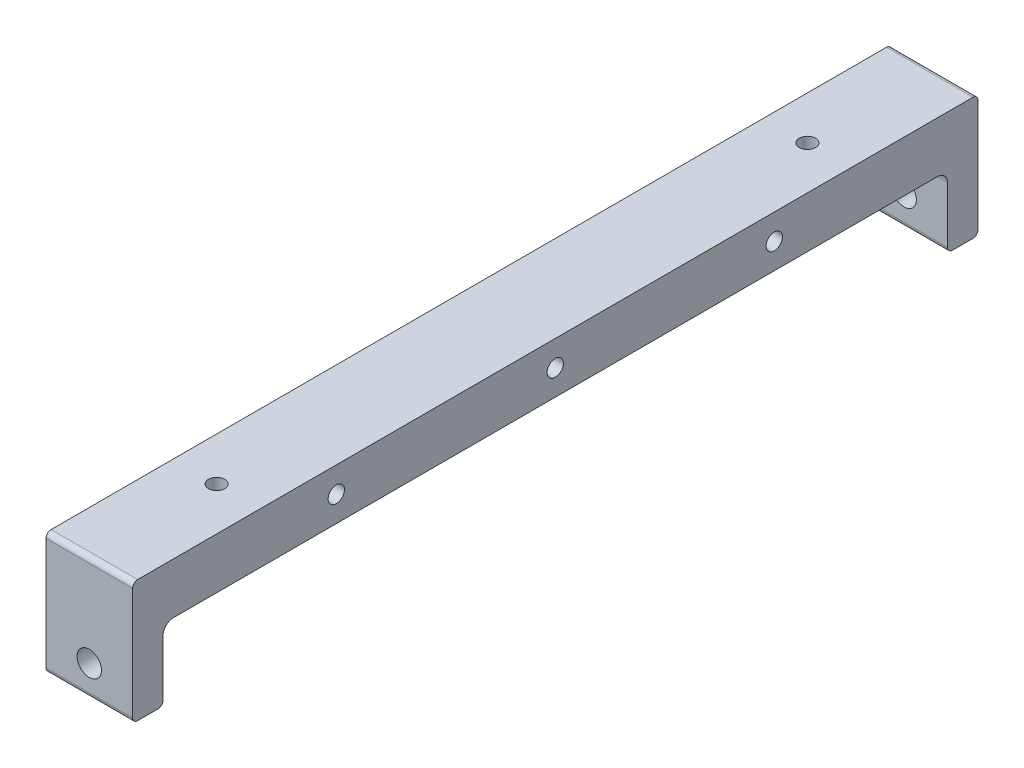
SolidWorks part; units mm, degrees
material "6061 Alloy"
ref_plane "Frontal" through (0, 0, 0) normal (0, 0, 1) x (1, 0, 0)
ref_plane "Superior" through (0, 0, 0) normal (0, 1, 0) x (1, 0, 0)
ref_plane "Direito" through (0, 0, 0) normal (1, 0, 0) x (0, 0, -1)
sketch "Sketch1" plane through (0, 0, 0) normal (0, 0, 1) x (1, 0, 0)
  line L1 (-4.25, -6) -> (4.25, -6)
  line L2 (-4.25, -6) -> (-4.25, 6)
  line L3 (-4.25, 6) -> (4.25, 6)
  line L4 (4.25, -6) -> (4.25, 6)
  line L5 (-4.25, -6) -> (4.25, 6) construction
  line L6 (-4.25, 6) -> (4.25, -6) construction
  point P0 (0, 0)
  dimension "D1" = 8.5
  dimension "D2" = 12
extrude "Boss-Extrude1" add sketch "Sketch1" along normal mid plane 83
sketch "Sketch2" plane through (4.25, 0, 0) normal (1, 0, 0) x (0, 0, -1)
  line L0 (-37.5, 1) -> (37.5, 1)
  line L1 (38.5, 0) -> (38.5, -6)
  line L2 (-41.5, -6) -> (41.5, -6) construction
  line L3 (38.5, -6) -> (-38.5, -6)
  line L4 (-38.5, -6) -> (-38.5, 0)
  line L5 (-41.5, 6) -> (41.5, 6) construction
  line L6 (-41.5, -6) -> (-41.5, 6) construction
  line L7 (41.5, -6) -> (41.5, 6) construction
  arc A0 (37.5, 1) -> (38.5, 0) centre (37.5, 0) cw
  arc A1 (-37.5, 1) -> (-38.5, 0) centre (-37.5, 0) ccw
  dimension "D4" = 1
  dimension "D5" = 1
  dimension "D1" = 5
  dimension "D2" = 3
  dimension "D3" = 3
extrude "Cut-Extrude1" cut sketch "Sketch2" against normal through all
fillet "Fillet1" radius 0.5 6 edges at (0, -6, 38.5) (0, -6, 41.5) (0, -6, -38.5) (0, -6, -41.5) (0, 6, 41.5) (0, 6, -41.5)
hole_wizard "M2 Hole1-R" positions "Sketch19" profile "Sketch18" hole size "M2" standard "DIN"
sketch "Sketch19" plane through (4.25, 0, 0) normal (1, 0, 0) x (0, 0, -1)
  line L0 (-41.5, -5.5) -> (-41.5, 5.5) construction
  line L1 (41.5, -5.5) -> (41.5, 5.5) construction
  line L2 (-41, 6) -> (41, 6) construction
  point P0 (21.5, 3.5)
  point P2 (-21.5, 3.5)
  dimension "D1" = 20
  dimension "D2" = 20
  dimension "D3" = 2.5
sketch "Sketch18" plane through (4.25, 3.5, -21.5) normal (0, 1, 0) x (0, 0, -1)
  line L0 (0, 0) -> (0, 5.4807)
  line L1 (0, 5.4807) -> (0.8, 5)
  line L2 (0.8, 5) -> (0.8, 0)
  line L5 (0.8, 0) -> (0, 0)
  line L10 (0, 5.4807) -> (-0.8, 5) construction
  line L11 (0, -6.35) -> (0, 107.95) construction
  dimension "Hole Dia." = 1.6
  dimension "Hole Depth" = 5
  dimension "Drill Angle" = 118
hole_wizard "M2 Hole2-T" positions "Sketch13" profile "Sketch12" hole size "M2" standard "DIN"
sketch "Sketch13" plane through (4.25, 0, 0) normal (1, 0, 0) x (0, 0, -1)
  line L0 (-41, 6) -> (41, 6) construction
  point P0 (0, 3.5)
  dimension "D1" = 2.5
sketch "Sketch12" plane through (4.25, 3.5, 0) normal (0, 1, 0) x (0, 0, -1)
  line L0 (0, 0) -> (0, 4.4807)
  line L1 (0, 4.4807) -> (0.8, 4)
  line L2 (0.8, 4) -> (0.8, 0)
  line L5 (0.8, 0) -> (0, 0)
  line L10 (0, 4.4807) -> (-0.8, 4) construction
  line L11 (0, -6.35) -> (0, 107.95) construction
  dimension "Hole Dia." = 1.6
  dimension "Hole Depth" = 4
  dimension "Drill Angle" = 118
hole_wizard "M2 Hole3-U" positions "Sketch8" profile "Sketch7" hole size "M2" standard "DIN"
sketch "Sketch8" plane through (0, 0, 41.5) normal (0, 0, 1) x (1, 0, 0)
  line L0 (4.25, -6) -> (-4.25, -6) construction
  point P0 (0, -3)
  dimension "D1" = 3
sketch "Sketch7" plane through (0, -3, 41.5) normal (1, 0, 0) x (0, -1, 0)
  line L0 (0, 0) -> (0, 10.721)
  line L1 (0, 10.721) -> (1.2, 10)
  line L2 (1.2, 10) -> (1.2, 0)
  line L5 (1.2, 0) -> (0, 0)
  line L10 (0, 10.721) -> (-1.2, 10) construction
  line L11 (0, -6.35) -> (0, 107.95) construction
  dimension "Hole Dia." = 2.4
  dimension "Hole Depth" = 10
  dimension "Drill Angle" = 118
hole_wizard "M2 Hole4-V" positions "Sketch15" profile "Sketch14" hole size "M2" standard "DIN" end condition through all
sketch "Sketch15" plane through (0, 6, 0) normal (0, 1, 0) x (1, 0, 0)
  line L0 (4.25, -41) -> (4.25, 41) construction
  line L1 (-4.25, 41.5) -> (4.25, 41.5) construction
  line L2 (4.25, -41.5) -> (-4.25, -41.5) construction
  point P0 (0, 29)
  point P2 (0, -29)
  dimension "D1" = 4.25
  dimension "D2" = 12.5
  dimension "D3" = 12.5
sketch "Sketch14" plane through (0, 6, -29) normal (1, 0, 0) x (0, 0, 1)
  line L0 (0, 0) -> (0, 12)
  line L1 (0, 12) -> (0.8, 12)
  line L2 (0.8, 12) -> (0.8, 0)
  line L5 (0.8, 0) -> (0, 0)
  line L11 (0, -6.35) -> (0, 107.95) construction
  dimension "Thru Hole Dia." = 1.6
  dimension "Thru Hole Depth" = 12
hole_wizard "M2 Hole5-W" positions "Sketch10" profile "Sketch9" hole size "M2" standard "DIN"
sketch "Sketch10" plane through (-4.25, 0, 0) normal (-1, 0, 0) x (0, 0, 1)
  line L0 (41, 6) -> (-41, 6) construction
  line L1 (41.5, 5.5) -> (41.5, -5.5) construction
  line L2 (-41.5, 5.5) -> (-41.5, -5.5) construction
  point P0 (-35.5, 3.5)
  point P2 (35.5, 3.5)
  dimension "D1" = 2.5
  dimension "D2" = 6
  dimension "D3" = 6
sketch "Sketch9" plane through (-4.25, 3.5, -35.5) normal (0, 1, 0) x (0, 0, 1)
  line L0 (0, 0) -> (0, 5.4807)
  line L1 (0, 5.4807) -> (0.8, 5)
  line L2 (0.8, 5) -> (0.8, 0)
  line L5 (0.8, 0) -> (0, 0)
  line L10 (0, 5.4807) -> (-0.8, 5) construction
  line L11 (0, -6.35) -> (0, 107.95) construction
  dimension "Hole Dia." = 1.6
  dimension "Hole Depth" = 5
  dimension "Drill Angle" = 118
hole_wizard "M2 Hole6-Y" positions "Sketch17" profile "Sketch16" hole size "M2" standard "DIN"
sketch "Sketch17" plane through (0, 0, -41.5) normal (0, 0, -1) x (-1, 0, 0)
  line L0 (4.25, 5.5) -> (4.25, -5.5) construction
  line L1 (-4.25, 6) -> (4.25, 6) construction
  point P0 (0, -3)
  dimension "D1" = 4.25
  dimension "D2" = 9
sketch "Sketch16" plane through (0, -3, -41.5) normal (1, 0, 0) x (0, 1, 0)
  line L0 (0, 0) -> (0, 10.721)
  line L1 (0, 10.721) -> (1.2, 10)
  line L2 (1.2, 10) -> (1.2, 0)
  line L5 (1.2, 0) -> (0, 0)
  line L10 (0, 10.721) -> (-1.2, 10) construction
  line L11 (0, -6.35) -> (0, 107.95) construction
  dimension "Hole Dia." = 2.4
  dimension "Hole Depth" = 10
  dimension "Drill Angle" = 118
